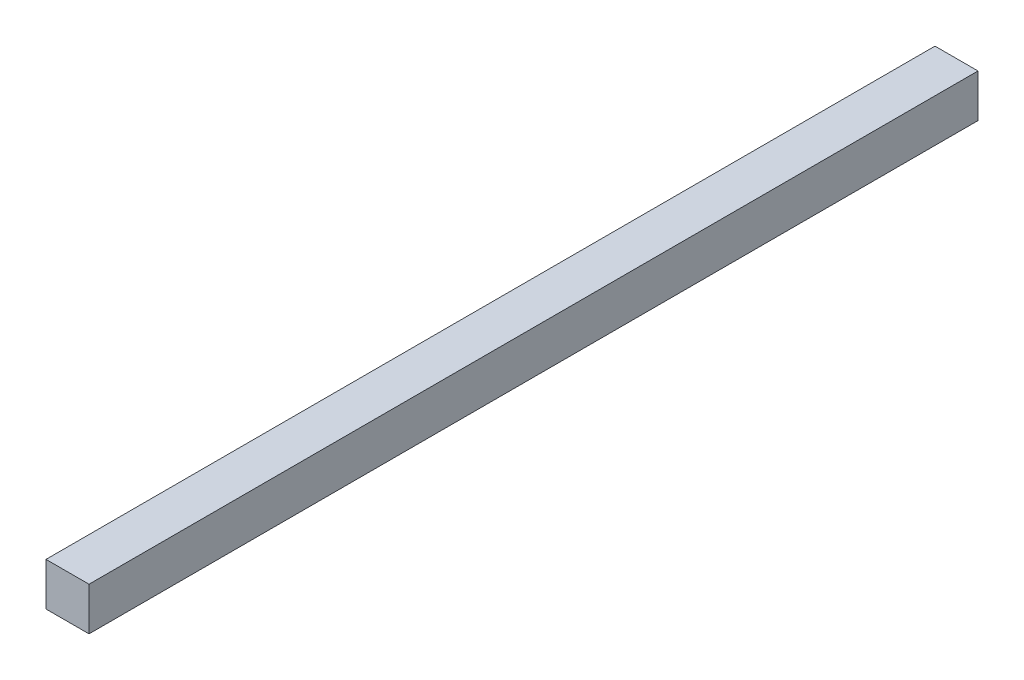
SolidWorks part; units mm, degrees
ref_plane "前视基准面" through (0, 0, 0) normal (0, 0, 1) x (1, 0, 0)
ref_plane "上视基准面" through (0, 0, 0) normal (0, 1, 0) x (1, 0, 0)
ref_plane "右视基准面" through (0, 0, 0) normal (1, 0, 0) x (0, 0, -1)
sketch "草图6" plane through (0, 0, 0) normal (0, 0, 1) x (1, 0, 0)
  line L1 (-12.2596, 28.4856) -> (2.7404, 28.4856)
  line L2 (-12.2596, 28.4856) -> (-12.2596, 43.4856)
  line L3 (-12.2596, 43.4856) -> (2.7404, 43.4856)
  line L4 (2.7404, 28.4856) -> (2.7404, 43.4856)
  dimension "D1" = 15
  dimension "D2" = 15
extrude "凸台-拉伸2" add sketch "草图6" along normal blind 310
